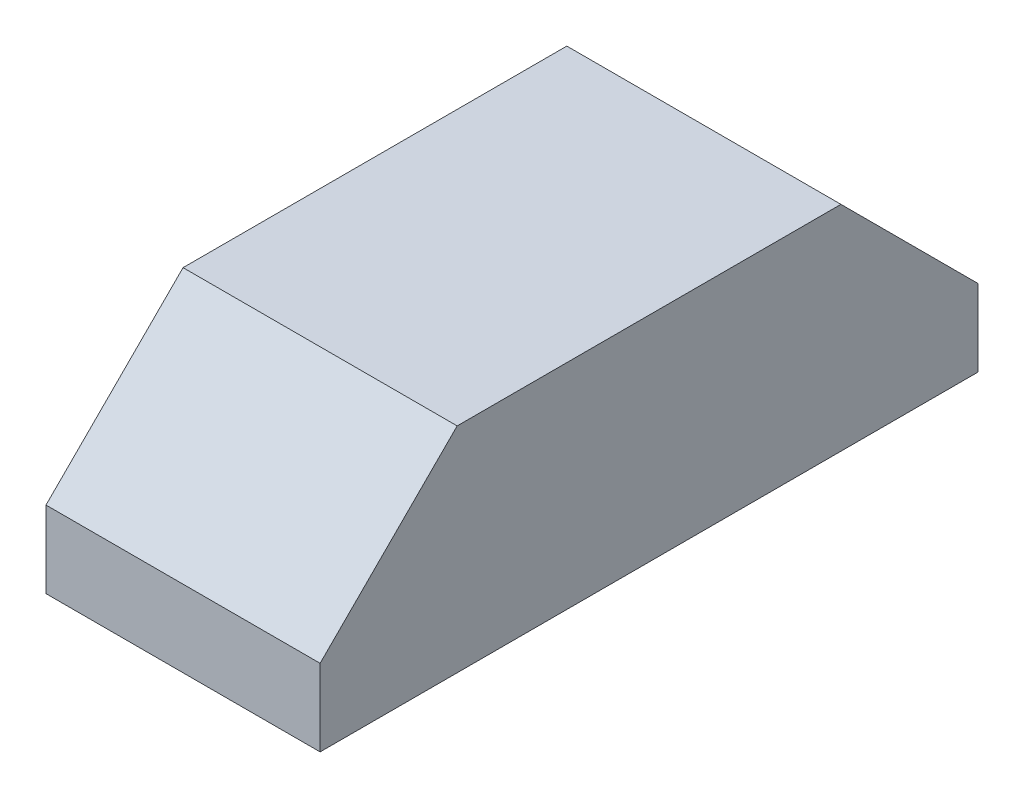
SolidWorks part; units mm, degrees
material "1060 Alloy"
ref_plane "Front Plane" through (0, 0, 0) normal (0, 0, 1) x (1, 0, 0)
ref_plane "Top Plane" through (0, 0, 0) normal (0, 1, 0) x (1, 0, 0)
ref_plane "Right Plane" through (0, 0, 0) normal (1, 0, 0) x (0, 0, -1)
sketch "Sketch1" plane through (0, 0, 0) normal (1, 0, 0) x (0, 0, -1)
  line L0 (55, 0) -> (-55, 0) construction
  line L1 (-19.4943, 0) -> (-7.4943, 0)
  line L2 (-19.4943, 0) -> (-19.4943, 1.4)
  line L4 (-7.4943, 0) -> (-7.4943, 1.4)
  line L5 (-19.4943, 1.4) -> (-16.9943, 3.9)
  line L6 (-16.9943, 3.9) -> (-9.9943, 3.9)
  line L7 (-9.9943, 3.9) -> (-7.4943, 1.4)
  dimension "D1" = 12
  dimension "D2" = 1.4
  dimension "D3" = 1.4
  dimension "D4" = 45
  dimension "D5" = 2.5
  dimension "D6" = 2.5
extrude "Boss-Extrude1" add sketch "Sketch1" along normal blind 5
hole_wizard "Ø3.0mm Dowel Hole1" positions "Sketch2" profile "Sketch3" hole size "Ø3.0" standard "ISO"
sketch "Sketch2" plane through (0, 0, 0) normal (0, -1, 0) x (-1, 0, 0)
  line L0 (-5, -19.4943) -> (-5, -7.4943) construction
  line L1 (-5, -7.4943) -> (0, -7.4943) construction
  point P0 (-2.5, -13.4943)
  dimension "D1" = 2.5
  dimension "D2" = 6
sketch "Sketch3" plane through (2.5, 0, 13.4943) normal (1, 0, 0) x (0, 0, -1)
  line L0 (0, 0) -> (0, 2.9013)
  line L1 (0, 2.9013) -> (1.5, 2)
  line L2 (1.5, 2) -> (1.5, 0)
  line L5 (1.5, 0) -> (0, 0)
  line L10 (0, 2.9013) -> (-1.5, 2) construction
  line L11 (0, -6.35) -> (0, 107.95) construction
  dimension "Hole Dia." = 3
  dimension "Hole Depth" = 2
  dimension "Drill Angle" = 118
equation "\"width\"=2.5"
equation "\"D5@Sketch1\"=\"width\""
equation "\"D6@Sketch1\"=\"width\""
